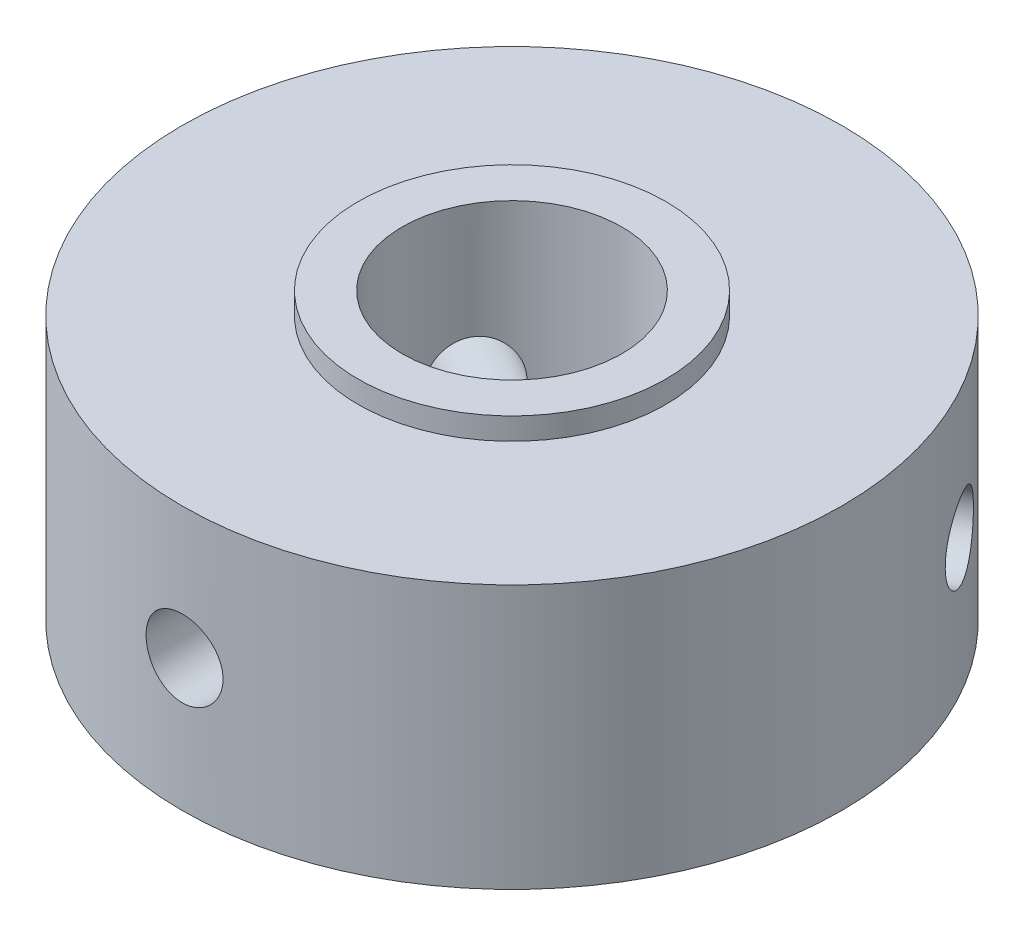
SolidWorks part; units mm, degrees
ref_plane "Front Plane" through (0, 0, 0) normal (0, 0, 1) x (1, 0, 0)
ref_plane "Top Plane" through (0, 0, 0) normal (0, 1, 0) x (1, 0, 0)
ref_plane "Right Plane" through (0, 0, 0) normal (1, 0, 0) x (0, 0, -1)
sketch "Sketch1" plane through (0, 0, 0) normal (0, 1, 0) x (1, 0, 0)
  circle A0 centre (0, 0) radius 15
  dimension "D1" = 30
extrude "Boss-Extrude1" add sketch "Sketch1" along normal blind 12 contours A0
sketch "Sketch2" plane through (0, 12, 0) normal (0, 1, 0) x (1, 0, 0)
  circle A0 centre (0, 0) radius 5
  dimension "D1" = 10
sketch "Sketch8" plane through (0, 0, 0) normal (0, 0, 1) x (1, 0, 0)
  line L0 (0, 0) -> (0, 6.8237) construction
  line L1 (0, 0) -> (16.8014, 0) construction
sketch "Sketch13" plane through (0, 0, 0) normal (0, 1, 0) x (1, 0, 0)
  circle A0 centre (0, 0) radius 7
  circle A1 centre (0, 0) radius 5 construction
  dimension "D1" = 2
extrude "Boss-Extrude3" add sketch "Sketch13" along normal blind 13
extrude "Cut-Extrude2" cut sketch "Sketch2" against normal through all both and the other way through all
ref_plane "Plane2" through (0, 0, 15) normal (0, 0, 1) x (1, 0, 0)
hole_wizard "Ø4.0mm Dowel Hole1" positions "Sketch15" profile "Sketch16" hole size "Ø4.0" standard "ANSI Metric"
sketch "Sketch15" plane through (0, 0, 15) normal (0, 0, 1) x (1, 0, 0)
  line L0 (0, 0) -> (0, 6.8237) construction
  line L1 (-15, 0) -> (15, 0) construction
  point P0 (0, 6)
  dimension "D1" = 6
sketch "Sketch16" plane through (0, 6, 15) normal (1, 0, 0) x (0, -1, 0)
  line L0 (0, 0) -> (0, 16.0505)
  line L1 (0, 16.0505) -> (1.75, 14.999)
  line L2 (1.75, 14.999) -> (1.75, 0)
  line L5 (1.75, 0) -> (0, 0)
  line L10 (0, 16.0505) -> (-1.75, 14.999) construction
  line L11 (0, -6.35) -> (0, 107.95) construction
  dimension "Hole Dia." = 3.5
  dimension "Hole Depth" = 14.999
  dimension "Drill Angle" = 118
pattern_circular "CirPattern1" count 3 over 360 about axis through (0, 0, 0) along (0, 1, 0) of "Ø4.0mm Dowel Hole1"
equation "\"D1@Sketch15\"=12/2"
